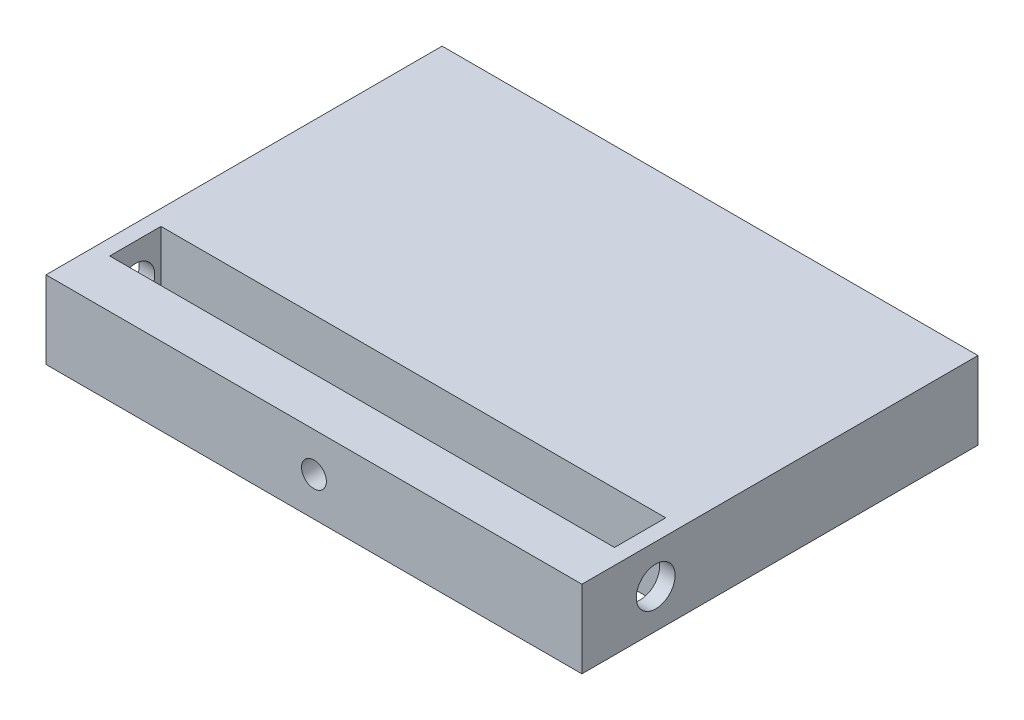
SolidWorks part; units mm, degrees
material "6061 合金"
ref_plane "前视基准面" through (0, 0, 0) normal (0, 0, 1) x (1, 0, 0)
ref_plane "上视基准面" through (0, 0, 0) normal (0, 1, 0) x (1, 0, 0)
ref_plane "右视基准面" through (0, 0, 0) normal (1, 0, 0) x (0, 0, -1)
sketch "草图1" plane through (0, 0, 0) normal (0, 1, 0) x (1, 0, 0)
  line L1 (-17.25, 12.75) -> (17.25, 12.75)
  line L2 (-17.25, 12.75) -> (-17.25, -12.75)
  line L3 (-17.25, -12.75) -> (17.25, -12.75)
  line L4 (17.25, 12.75) -> (17.25, -12.75)
  line L5 (-17.25, 12.75) -> (17.25, -12.75) construction
  line L6 (-17.25, -12.75) -> (17.25, 12.75) construction
  point P0 (0, 0)
  dimension "D1" = 25.5
  dimension "D2" = 34.5
extrude "凸台-拉伸1" add sketch "草图1" along normal blind 5
sketch "草图5" plane through (0, 0, 0) normal (0, -1, 0) x (1, 0, 0)
  line L0 (0, 12.75) -> (0, -12.75) construction
  line L1 (-16.25, 6.35) -> (16.25, 6.35)
  line L2 (-16.25, 6.35) -> (-16.25, 9.65)
  line L3 (-16.25, 9.65) -> (16.25, 9.65)
  line L4 (16.25, 6.35) -> (16.25, 9.65)
  line L5 (-16.25, 6.35) -> (16.25, 9.65) construction
  line L6 (-16.25, 9.65) -> (16.25, 6.35) construction
  line L7 (-17.25, 12.75) -> (17.25, 12.75) construction
  line L8 (17.25, -12.75) -> (-17.25, -12.75) construction
  point P0 (0, 8)
  dimension "D1" = 32.5
  dimension "D2" = 3.3
  dimension "D3" = 16.25
  dimension "D4" = 3.1
extrude "切除-拉伸1" cut sketch "草图5" against normal through all
sketch "草图7" plane through (17.25, 0, 0) normal (1, 0, 0) x (0, 0, -1)
  line L0 (-12.75, 0) -> (12.75, 0) construction
  line L1 (-12.75, 5) -> (-12.75, 0) construction
  line L2 (0, 5) -> (0, 0) construction
  line L3 (-12.75, 5) -> (12.75, 5) construction
  circle A0 centre (-8, 2.5) radius 1.25
  dimension "D1" = 2.5
  dimension "D2" = 2.5
  dimension "D3" = 4.75
extrude "切除-拉伸2" cut sketch "草图7" against normal through all
hole_wizard "M2x0.4 螺纹孔1" positions "3D草图1" profile "草图8" tap size "M2x0.4" standard "ANSI Metric"
sketch3d "3D草图1"
  line L0 (17.25, 5, -12.75) -> (-17.25, 5, -12.75) construction
  line L1 (-17.25, 5, -12.75) -> (-17.25, 0, -12.75) construction
  point P0 (0, 2.5, -12.75)
  dimension "D1" = 2.5
  dimension "D2" = 17.25
sketch "草图8" plane through (0, 2.5, -12.75) normal (1, 0, 0) x (0, 1, 0)
  line L0 (0, 0) -> (0, 5.6807)
  line L1 (0, 5.6807) -> (0.8, 5.2)
  line L2 (0.8, 5.2) -> (0.8, 0)
  line L5 (0.8, 0) -> (0, 0)
  line L10 (0, 5.6807) -> (-0.8, 5.2) construction
  line L11 (0, -6.35) -> (0, 107.95) construction
  dimension "螺纹孔钻头直径" = 1.6
  dimension "螺纹孔钻头深度" = 5.2
  dimension "导头角度" = 118
cosmetic thread "孔螺蚊线1" parameters "D1"=4, "D2"=2
mirror "镜向1" about plane through (0, 0, 0) normal (0, 0, 1) of "M2x0.4 螺纹孔1"
